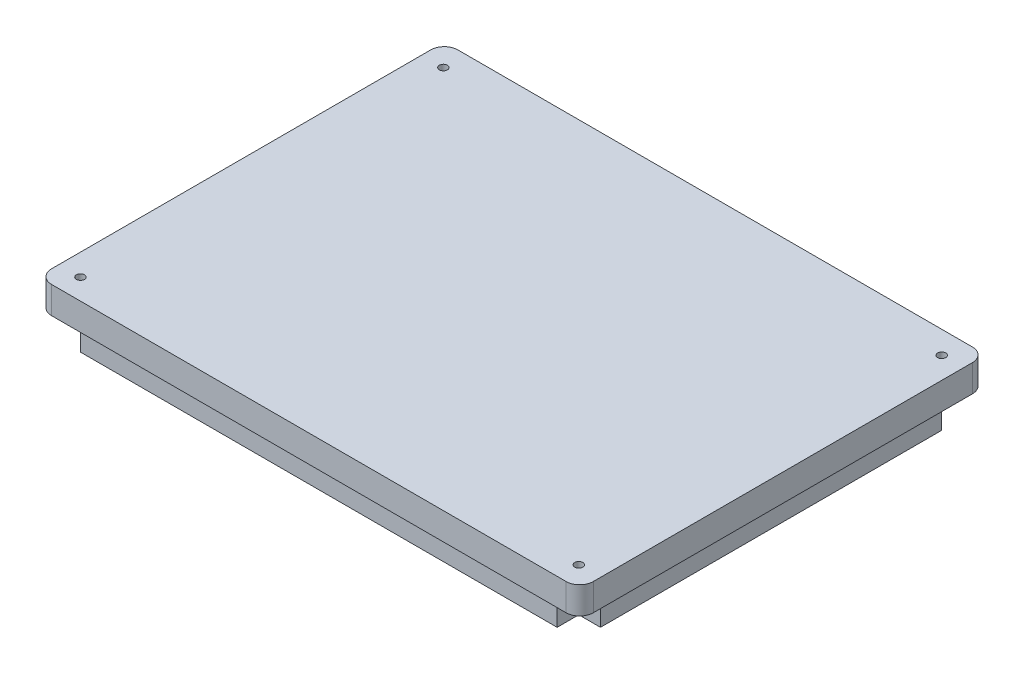
SolidWorks part; units mm, degrees
ref_plane "Płaszczyzna przednia" through (0, 0, 0) normal (0, 0, 1) x (1, 0, 0)
ref_plane "Płaszczyzna górna" through (0, 0, 0) normal (0, 1, 0) x (1, 0, 0)
ref_plane "Płaszczyzna prawa" through (0, 0, 0) normal (1, 0, 0) x (0, 0, -1)
sketch "Szkic1" plane through (0, 0, 0) normal (0, 1, 0) x (1, 0, 0)
  line L0 (-94.9815, 75.273) -> (95.0185, 75.273)
  line L1 (100.0185, 70.273) -> (100.0185, -69.727)
  line L2 (95.0185, -74.727) -> (-94.9815, -74.727)
  line L3 (-99.9815, 70.273) -> (-99.9815, -69.727)
  line L4 (-96, 63) -> (-88, 63)
  line L5 (-88, 63) -> (-88, 71)
  line L6 (-88, 71) -> (88, 71)
  line L7 (88, 71) -> (88, 63)
  line L8 (88, 63) -> (96, 63)
  line L9 (96, 63) -> (96, -63)
  line L10 (96, -63) -> (88, -63)
  line L11 (88, -63) -> (88, -71)
  line L12 (88, -71) -> (-88, -71)
  line L13 (-88, -71) -> (-88, -63)
  line L14 (-88, -63) -> (-96, -63)
  line L15 (-96, -63) -> (-96, 63)
  arc A0 (-99.9815, -69.727) -> (-94.9815, -74.727) centre (-94.9815, -69.727) ccw
  arc A1 (95.0185, -74.727) -> (100.0185, -69.727) centre (95.0185, -69.727) ccw
  arc A2 (95.0185, 75.273) -> (100.0185, 70.273) centre (95.0185, 70.273) cw
  arc A3 (-94.9815, 75.273) -> (-99.9815, 70.273) centre (-94.9815, 70.273) ccw
extrude "Dodanie-wyciągnięcie1" add sketch "Szkic1" along normal blind 10 contours L0 A2 L1 A1 L2 A0 L3 A3
sketch "Szkic4" plane through (0, 0, 0) normal (0, -1, 0) x (1, 0, 0)
  line L0 (0.0185, 74.727) -> (0, 0) construction
  line L1 (95.0185, 74.727) -> (-94.9815, 74.727) construction
  line L2 (-94.9815, 75.3168) -> (95.0185, 75.3168)
  line L3 (100.0185, 70.3168) -> (100.0185, -69.6832)
  line L4 (95.0185, -74.6832) -> (-94.9815, -74.6832)
  line L5 (-99.9815, 70.3168) -> (-99.9815, -69.6832)
  line L6 (-96, 63.0438) -> (-88, 63.0438)
  line L7 (-88, 63.0438) -> (-88, 71.0438)
  line L8 (-88, 71.0438) -> (88, 71.0438)
  line L9 (88, 71.0438) -> (88, 63.0438)
  line L10 (88, 63.0438) -> (96, 63.0438)
  line L11 (96, 63.0438) -> (96, -62.9562)
  line L12 (96, -62.9562) -> (88, -62.9562)
  line L13 (88, -62.9562) -> (88, -70.9562)
  line L14 (88, -70.9562) -> (-88, -70.9562)
  line L15 (-88, -70.9562) -> (-88, -62.9562)
  line L16 (-88, -62.9562) -> (-96, -62.9562)
  line L17 (-96, -62.9562) -> (-96, 63.0438)
  arc A0 (-99.9815, -69.6832) -> (-94.9815, -74.6832) centre (-94.9815, -69.6832) ccw
  arc A1 (95.0185, -74.6832) -> (100.0185, -69.6832) centre (95.0185, -69.6832) ccw
  arc A2 (95.0185, 75.3168) -> (100.0185, 70.3168) centre (95.0185, 70.3168) cw
  arc A3 (-94.9815, 75.3168) -> (-99.9815, 70.3168) centre (-94.9815, 70.3168) ccw
  point P5 (0, 0)
extrude "Dodanie-wyciągnięcie2" add sketch "Szkic4" along normal blind 10
sketch "Szkic5" plane through (0, 0, 0) normal (0, -1, 0) x (1, 0, 0)
  line L3 (96, -62.9562) -> (88, -62.9562) construction
  line L4 (-88, -70.9562) -> (-88, -62.9562) construction
  line L5 (-88, -62.9562) -> (-96, -62.9562) construction
  line L7 (-88, 63.0438) -> (-88, 71.0438) construction
  circle A0 centre (-92, -66.9562) radius 1.5
  circle A1 centre (-92, 67.0438) radius 1.5
  circle A2 centre (92, 67.0438) radius 1.5
  circle A3 centre (92, -66.9562) radius 1.5
  dimension "D1" = 3
  dimension "D2" = 3
  dimension "D3" = 3
  dimension "D4" = 3
  dimension "D5" = 4
  dimension "D6" = 4
  dimension "D7" = 4
  dimension "D8" = 4
extrude "Wytnij-wyciągnięcie1" cut sketch "Szkic5" against normal blind 15
